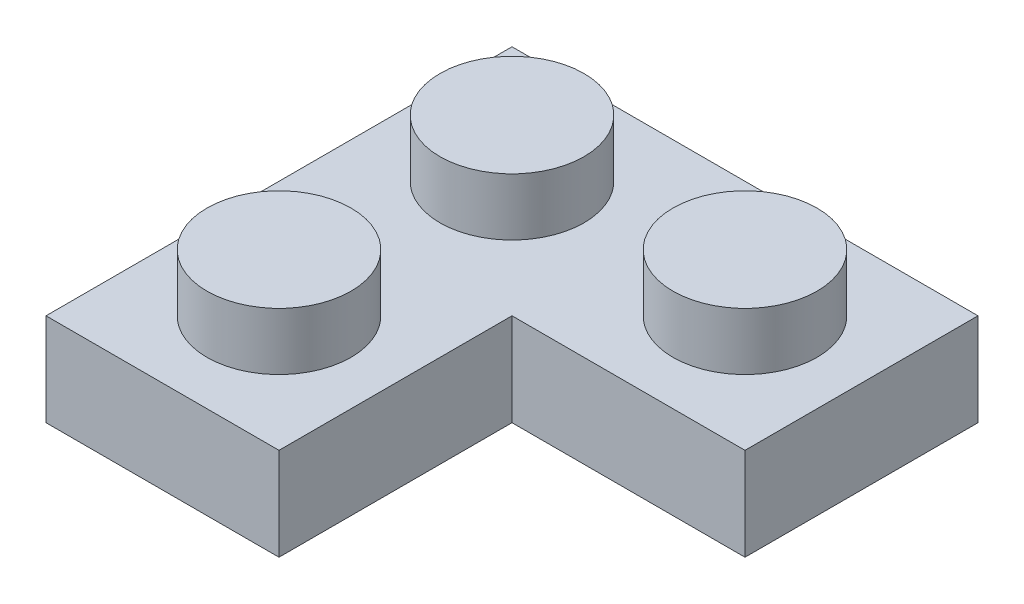
SolidWorks part; units mm, degrees
ref_plane "Front Plane" through (0, 0, 0) normal (0, 0, 1) x (1, 0, 0)
ref_plane "Top Plane" through (0, 0, 0) normal (0, 1, 0) x (1, 0, 0)
ref_plane "Right Plane" through (0, 0, 0) normal (1, 0, 0) x (0, 0, -1)
sketch "Sketch2" plane through (0, 0, 0) normal (0, 1, 0) x (1, 0, 0)
  line L0 (0, 0) -> (0, -7.925)
  line L1 (0, -7.925) -> (-7.925, -7.925)
  line L2 (-7.925, -7.925) -> (-7.925, 7.925)
  line L3 (-7.925, 7.925) -> (7.925, 7.925)
  line L4 (7.925, 7.925) -> (7.925, 0)
  line L5 (7.925, 0) -> (0, 0)
  point P3 (0, 0)
  point P8 (0, 7.925)
  point P9 (0, 0)
  point P10 (-7.925, 0)
  dimension "D1" = 15.85
  dimension "D2" = 15.85
extrude "Boss-Extrude1" add sketch "Sketch2" against normal blind 3.15
sketch "Sketch3" plane through (0, 0, 0) normal (0, 1, 0) x (1, 0, 0)
  line L0 (7.925, 7.925) -> (-7.925, 7.925) construction
  line L1 (7.925, 0) -> (7.925, 7.925) construction
  line L2 (-7.925, 7.925) -> (-7.925, -7.925) construction
  line L3 (-7.925, -7.925) -> (0, -7.925) construction
  circle A0 centre (-3.9625, 3.9625) radius 2.45
  circle A1 centre (3.9625, 3.9625) radius 2.45
  circle A2 centre (-3.9625, -3.9625) radius 2.45
  dimension "D1" = 4.9
  dimension "D2" = 4.9
  dimension "D3" = 4.9
  dimension "D4" = 3.9625
  dimension "D5" = 3.9625
  dimension "D6" = 3.9625
  dimension "D7" = 3.9625
  dimension "D8" = 3.9625
  dimension "D9" = 3.9625
extrude "Boss-Extrude2" add sketch "Sketch3" along normal blind 1.95
shell "Shell1" thickness 1.5
